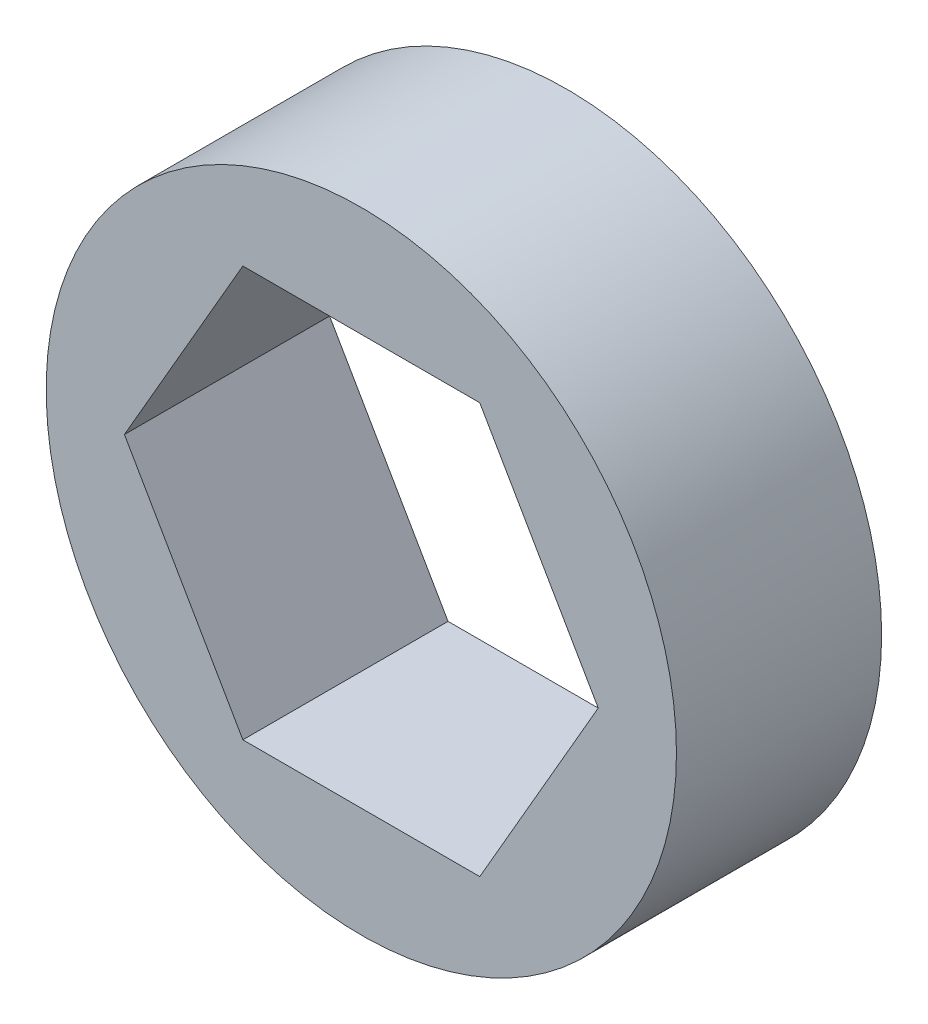
SolidWorks part; units mm, degrees
material "Birch Plywood"
ref_plane "Front Plane" through (0, 0, 0) normal (0, 0, 1) x (1, 0, 0)
ref_plane "Top Plane" through (0, 0, 0) normal (0, 1, 0) x (1, 0, 0)
ref_plane "Right Plane" through (0, 0, 0) normal (1, 0, 0) x (0, 0, -1)
sketch "Sketch1" plane through (0, 0, 0) normal (0, 0, 1) x (1, 0, 0)
  line L1 (-7.3323, 0) -> (-3.6662, -6.35)
  line L2 (-3.6662, -6.35) -> (3.6662, -6.35)
  line L3 (3.6662, -6.35) -> (7.3323, 0)
  line L4 (7.3323, 0) -> (3.6662, 6.35)
  line L5 (3.6662, 6.35) -> (-3.6662, 6.35)
  line L6 (-3.6662, 6.35) -> (-7.3323, 0)
  circle A0 centre (0, 0) radius 9.7536
  circle A1 centre (0, 0) radius 6.35 construction
  dimension "D1" = 12.7
  dimension "D2" = 19.5072
extrude "Boss-Extrude1" add sketch "Sketch1" along normal blind 6.35
equation "\"D1@.25inTabsWithHoleShort\"=.33"
